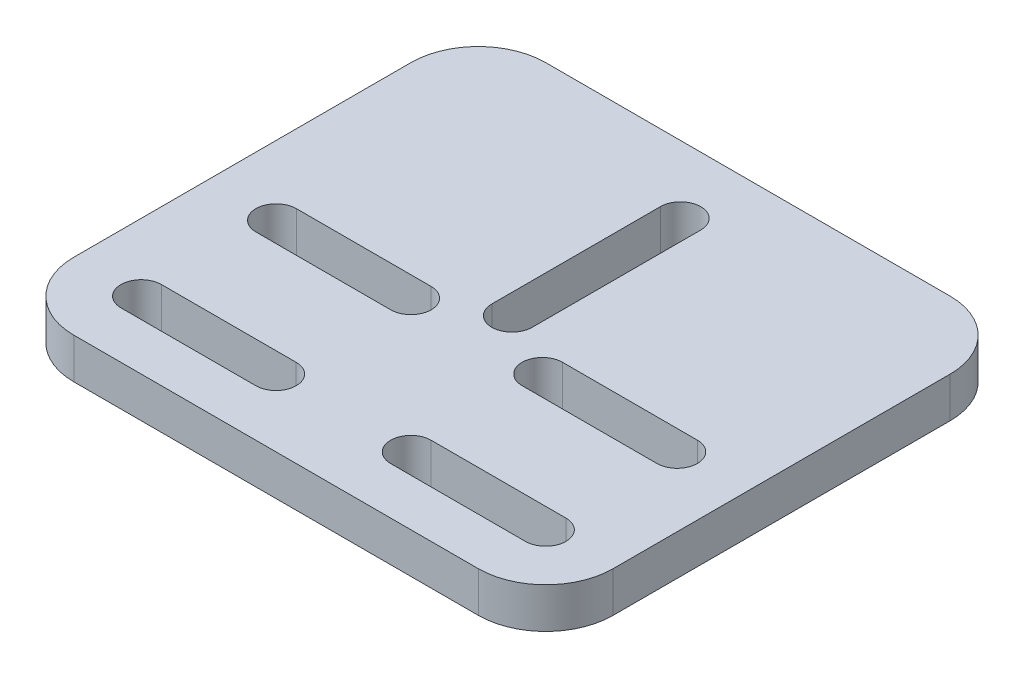
SolidWorks part; units mm, degrees
ref_plane "前视基准面" through (0, 0, 0) normal (0, 0, 1) x (1, 0, 0)
ref_plane "上视基准面" through (0, 0, 0) normal (0, 1, 0) x (1, 0, 0)
ref_plane "右视基准面" through (0, 0, 0) normal (1, 0, 0) x (0, 0, -1)
sketch "草图1" plane through (0, 0, 0) normal (0, 1, 0) x (1, 0, 0)
  line L0 (-15, 12.5) -> (-15, -12.5) construction
  line L1 (-15, 17.5) -> (15, 17.5)
  line L2 (-20, 12.5) -> (-20, -12.5)
  line L3 (-15, -17.5) -> (15, -17.5)
  line L4 (20, 12.5) -> (20, -12.5)
  line L5 (-20, 17.5) -> (20, -17.5) construction
  line L6 (-20, -17.5) -> (20, 17.5) construction
  line L9 (-20, 0) -> (20, 0) construction
  line L10 (0, 17.5) -> (0, -17.5) construction
  line L13 (5, -11) -> (15, -11)
  line L14 (15, -14) -> (5, -14)
  line L15 (-15, -14) -> (-5, -14)
  line L16 (-5, -11) -> (-15, -11)
  line L17 (0, 17.5) -> (0, 12.5) construction
  line L18 (0, 12.5) -> (0, 17.5)
  line L21 (-15, -12.5) -> (-15, -2.5) construction
  line L22 (-15, -2.5) -> (-10, -2.5) construction
  line L23 (-14.8699, -1.1218) -> (-4.8699, -1.1218)
  line L24 (-4.8699, -4.1218) -> (-14.8699, -4.1218)
  line L25 (4.8699, -4.1218) -> (14.8699, -4.1218)
  line L26 (14.8699, -1.1218) -> (4.8699, -1.1218)
  line L27 (-1.5, 12.5) -> (-1.5, 0)
  line L28 (1.5, 12.5) -> (1.5, 0)
  arc A0 (-20, -12.5) -> (-15, -17.5) centre (-15, -12.5) ccw
  arc A1 (15, -17.5) -> (20, -12.5) centre (15, -12.5) ccw
  arc A2 (15, 17.5) -> (20, 12.5) centre (15, 12.5) cw
  arc A3 (-15, 17.5) -> (-20, 12.5) centre (-15, 12.5) ccw
  arc A8 (15, -14) -> (15, -11) centre (15, -12.5) ccw
  arc A9 (5, -11) -> (5, -14) centre (5, -12.5) ccw
  arc A10 (-5, -11) -> (-5, -14) centre (-5, -12.5) cw
  arc A11 (-15, -14) -> (-15, -11) centre (-15, -12.5) cw
  arc A12 (1.5, 12.5) -> (-1.5, 12.5) centre (0, 12.5) ccw
  arc A14 (-14.8699, -1.1218) -> (-14.8699, -4.1218) centre (-14.8699, -2.6218) ccw
  arc A15 (-4.8699, -4.1218) -> (-4.8699, -1.1218) centre (-4.8699, -2.6218) ccw
  arc A16 (14.8699, -1.1218) -> (14.8699, -4.1218) centre (14.8699, -2.6218) cw
  arc A17 (4.8699, -4.1218) -> (4.8699, -1.1218) centre (4.8699, -2.6218) cw
  arc A18 (-1.5, 0) -> (1.5, 0) centre (0, 0) ccw
  point P0 (0, 0)
  point P48 (1.5, 0)
  point P49 (-1.5, 0)
  dimension "D3" = 5
  dimension "D7" = 3
  dimension "D1" = 40
  dimension "D2" = 35
  dimension "D6" = 5
  dimension "D8" = 10
extrude "凸台-拉伸1" add sketch "草图1" along normal blind 3
